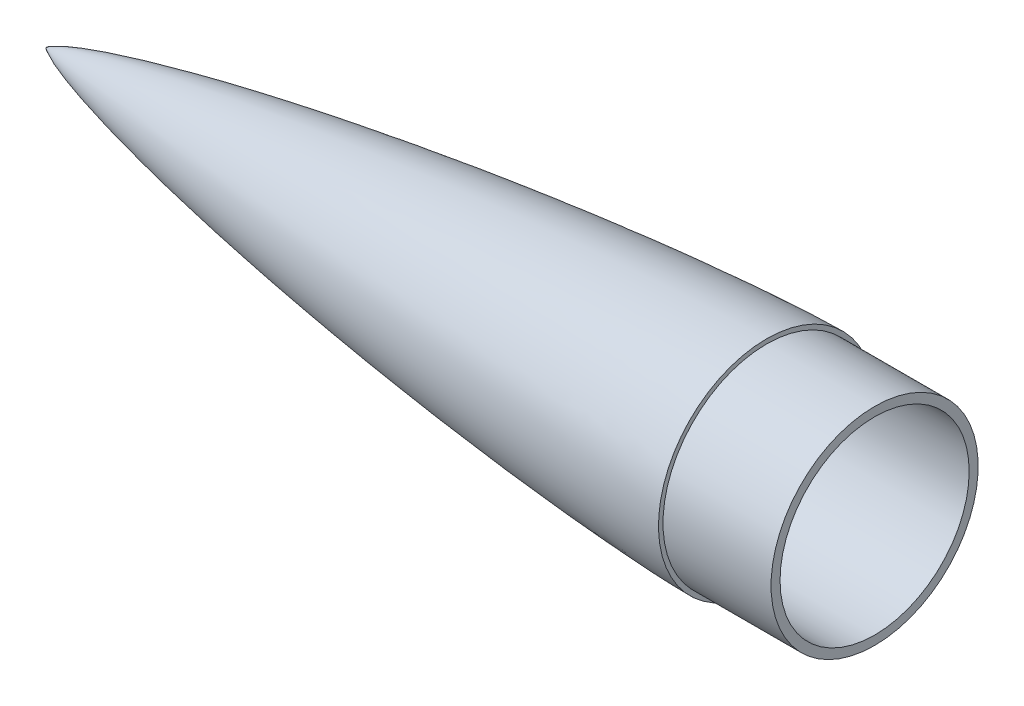
SolidWorks part; units mm, degrees
ref_plane "Front Plane" through (0, 0, 0) normal (0, 0, 1) x (1, 0, 0)
ref_plane "Top Plane" through (0, 0, 0) normal (0, 1, 0) x (1, 0, 0)
ref_plane "Right Plane" through (0, 0, 0) normal (1, 0, 0) x (0, 0, -1)
sketch "Sketch8" plane through (0, 0, 0) normal (0, 0, 1) x (1, 0, 0)
  line L1 (508, 0) -> (508, 76.2) construction
  line L4 (482.6, 72.1214) -> (482.6, 66.675)
  line L5 (482.6, 66.675) -> (584.2, 66.675)
  line L6 (584.2, 66.675) -> (584.2, 73.025)
  line L7 (584.2, 73.025) -> (508, 73.025)
  line L8 (508, 76.2) -> (508, 73.025)
  line L9 (6.35, 0) -> (0, 0)
  line L10 (508, 0) -> (6.35, 0) construction
  spline S0 degree 4 poles (0, 0) (0.0029, 0.0111) (0.0103, 0.0327) (0.0322, 0.0731) (0.071, 0.1297) (0.1211, 0.1922) (0.1925, 0.2713) (0.2786, 0.3574) (0.4074, 0.4757) (0.6103, 0.6446) (0.9241, 0.8805) (1.4561, 1.2392) (2.3534, 1.7778) (3.9321, 2.615) (6.8111, 3.9503) (11.9815, 6.0282) (20.5953, 9.0159) (32.2146, 12.5186) (46.1695, 16.2796) (65.4133, 21.0119) (88.6854, 26.1964) (116.1503, 31.7518) (147.8191, 37.5721) (179.5688, 42.9312) (211.3834, 47.889) (243.2525, 52.4831) (275.1689, 56.7353) (307.1277, 60.6563) (339.1253, 64.2468) (371.1593, 67.4978) (403.2279, 70.3877) (431.3176, 72.5657) (455.4154, 74.1378) (474.5447, 75.1535) (487.1684, 75.6937) (497.302, 76.0213) (503.4147, 76.1526) (506.4715, 76.1946) (508, 76.2) knots 0 0 0 0 0 0.000089 0.000177 0.000355 0.000532 0.000709 0.001004 0.001299 0.001888 0.002757 0.004048 0.006275 0.010003 0.016613 0.028658 0.049486 0.080709 0.110739 0.140768 0.203215 0.265661 0.328107 0.390553 0.452999 0.515445 0.577892 0.640338 0.702784 0.76523 0.827676 0.890122 0.921346 0.952569 0.976284 0.988142 1 1 1 1 1 construction
  spline S1 degree 4 poles (0, 0) (0.0029, 0.0111) (0.0103, 0.0327) (0.0322, 0.0731) (0.071, 0.1297) (0.1211, 0.1922) (0.1925, 0.2713) (0.2786, 0.3574) (0.4074, 0.4757) (0.6103, 0.6446) (0.9241, 0.8805) (1.4561, 1.2392) (2.3534, 1.7778) (3.9321, 2.615) (6.8111, 3.9503) (11.9815, 6.0282) (20.5953, 9.0159) (32.2146, 12.5186) (46.1695, 16.2796) (65.4133, 21.0119) (88.6854, 26.1964) (116.1503, 31.7518) (147.8191, 37.5721) (179.5688, 42.9312) (211.3834, 47.889) (243.2525, 52.4831) (275.1689, 56.7353) (307.1277, 60.6563) (339.1253, 64.2468) (371.1593, 67.4978) (403.2279, 70.3877) (431.3176, 72.5657) (455.4154, 74.1378) (474.5447, 75.1535) (487.1684, 75.6937) (497.302, 76.0213) (503.4147, 76.1526) (506.4715, 76.1946) (508, 76.2) knots 0 0 0 0 0 0.000089 0.000177 0.000355 0.000532 0.000709 0.001004 0.001299 0.001888 0.002757 0.004048 0.006275 0.010003 0.016613 0.028658 0.049486 0.080709 0.110739 0.140768 0.203215 0.265661 0.328107 0.390553 0.452999 0.515445 0.577892 0.640338 0.702784 0.76523 0.827676 0.890122 0.921346 0.952569 0.976284 0.988142 1 1 1 1 1
  spline S3 degree 3 poles (6.35, 0) (8.7987, 0.9073) (13.7274, 2.6032) (23.7643, 5.7461) (36.4514, 9.3108) (51.8065, 13.2308) (72.3881, 18.0989) (98.2581, 23.6608) (129.4401, 29.7396) (160.7212, 35.3397) (202.5307, 42.2632) (254.9453, 50.0138) (318.0216, 58.0404) (370.7068, 63.6782) (412.916, 67.4841) (444.602, 69.9382) (467.8333, 71.3907) (480.5034, 72.0218) (482.6, 72.1214) knots 0.027272 0.027272 0.027272 0.027272 0.042373 0.057474 0.087677 0.117879 0.148081 0.208486 0.268891 0.329296 0.3897 0.51051 0.631319 0.752129 0.812534 0.872939 0.933343 0.945323 0.945323 0.945323 0.945323
  point P10 (0, 0)
  dimension "D1" = 76.2
  dimension "D2" = 508
  dimension "D3" = 3.175
  dimension "D4" = 6.35
  dimension "D5" = 76.2
  dimension "D6" = 6.35
  dimension "D7" = 25.4
  dimension "D8" = 5.4464
  dimension "D9" = 577.85
revolve "Revolve8" add sketch "Sketch8" angle 360 about L10
